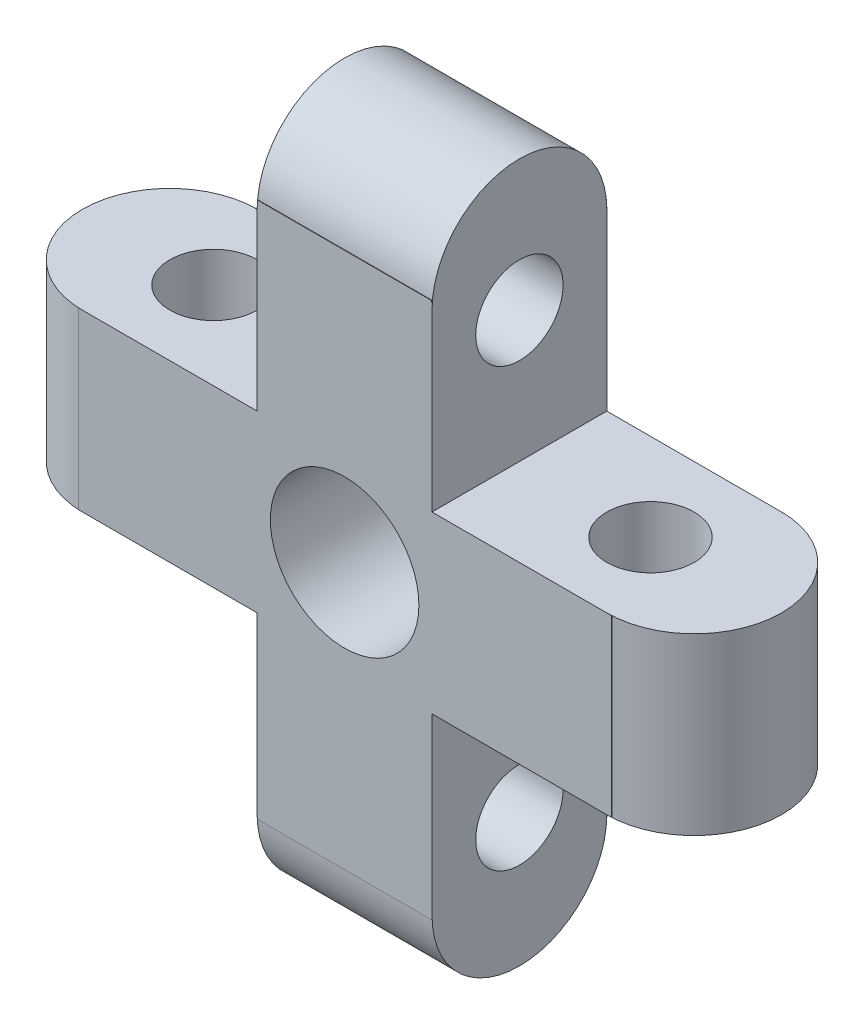
SolidWorks part; units mm, degrees
ref_plane "前视基准面" through (0, 0, 0) normal (0, 0, 1) x (1, 0, 0)
ref_plane "上视基准面" through (0, 0, 0) normal (0, 1, 0) x (1, 0, 0)
ref_plane "右视基准面" through (0, 0, 0) normal (1, 0, 0) x (0, 0, -1)
sketch "草图2" plane through (0, 0, 0) normal (0, 0, 1) x (1, 0, 0)
  line L0 (1.2374, 9.4816) -> (1.2374, 19.4816)
  line L1 (-8.7626, 9.4816) -> (1.2374, 9.4816)
  line L3 (-8.7626, -0.5184) -> (1.2374, -0.5184)
  line L5 (11.2374, 9.4816) -> (21.2374, 9.4816)
  line L8 (1.2374, -10.5184) -> (1.2374, -0.5184)
  line L10 (11.2374, -10.5184) -> (11.2374, -0.5184)
  line L14 (11.2374, -0.5184) -> (21.2374, -0.5184)
  line L18 (0, 0) -> (2.3667, -9.4816) construction
  line L19 (11.2374, 9.4816) -> (11.2374, 19.4816)
  line L20 (-8.7626, 9.4816) -> (1.2374, 9.4816)
  arc A0 (-8.7626, 9.4816) -> (-8.7626, -0.5184) centre (-8.7626, 4.4816) ccw
  arc A1 (21.2374, 9.4816) -> (21.2374, -0.5184) centre (21.2374, 4.4816) cw
  arc A2 (1.2374, -10.5184) -> (11.2374, -10.5184) centre (6.2374, -10.5184) ccw
  arc A3 (1.2374, 19.4816) -> (11.2374, 19.4816) centre (6.2374, 19.4816) cw
  point P0 (0, 0)
  point P5 (0, 0)
  dimension "D1" = 10
  dimension "D2" = 10
  dimension "D3" = 10
extrude "凸台-拉伸1" add sketch "草图2" along normal blind 10
sketch "草图3" plane through (0, -0.5184, 0) normal (0, -1, 0) x (1, 0, 0)
  line L0 (-8.7626, 0) -> (1.2374, 0) construction
  line L1 (1.2374, 0) -> (1.2374, 10) construction
  line L2 (1.2374, 10) -> (-8.7626, 10) construction
  line L3 (-13.7626, 0) -> (-8.7626, 0) construction
  line L4 (-8.7626, 10) -> (-13.7626, 10) construction
  line L5 (-8.7626, 10) -> (-8.7626, 0) construction
  line L6 (-8.7626, 0) -> (1.2374, 0)
  line L7 (1.2374, 0) -> (1.2374, 10)
  line L8 (1.2374, 10) -> (-8.7626, 10)
  line L9 (-13.7626, 0) -> (-8.7626, 0)
  line L10 (-8.7626, 10) -> (-13.7626, 10)
  line L11 (-8.7626, 10) -> (-8.7626, 0)
  line L12 (-13.7626, 10) -> (1.2374, 0)
  line L13 (-13.7626, 0) -> (1.2374, 10)
  circle A0 centre (-6.2626, 5) radius 2.5
  dimension "D1" = 5
extrude "切除-拉伸1" cut sketch "草图3" against normal blind 10 contours L12 A0 L13 | L12 A0 L13 | L13 A0 L12 | L13 A0 L12
sketch "草图4" plane through (11.2374, 0, 0) normal (1, 0, 0) x (0, 0, -1)
  line L0 (0, -15.5184) -> (0, -10.5184) construction
  line L1 (-10, -10.5184) -> (-10, -15.5184) construction
  line L2 (-10, -10.5184) -> (0, -10.5184) construction
  line L3 (0, -10.5184) -> (0, -0.5184) construction
  line L4 (0, -0.5184) -> (-10, -0.5184) construction
  line L5 (-10, -0.5184) -> (-10, -10.5184) construction
  line L6 (0, -15.5184) -> (0, -10.5184)
  line L7 (-10, -10.5184) -> (-10, -15.5184)
  line L8 (-10, -10.5184) -> (0, -10.5184)
  line L9 (0, -10.5184) -> (0, -0.5184)
  line L10 (0, -0.5184) -> (-10, -0.5184)
  line L11 (-10, -0.5184) -> (-10, -10.5184)
  line L12 (-10, -15.5184) -> (0, -0.5184)
  line L13 (0, -15.5184) -> (-10, -0.5184)
  circle A0 centre (-5, -8.0184) radius 2.5
  dimension "D1" = 5
extrude "切除-拉伸2" cut sketch "草图4" against normal blind 10 contours L13 A0 L12 | L12 A0 L13 | L13 A0 L12 | L12 A0 L13
sketch "草图5" plane through (0, 9.4816, 0) normal (0, 1, 0) x (1, 0, 0)
  line L0 (26.2374, 0) -> (21.2374, 0) construction
  line L1 (21.2374, -10) -> (26.2374, -10) construction
  line L2 (21.2374, -10) -> (21.2374, 0) construction
  line L3 (21.2374, 0) -> (11.2374, 0) construction
  line L4 (11.2374, 0) -> (11.2374, -10) construction
  line L5 (11.2374, -10) -> (21.2374, -10) construction
  line L6 (26.2374, 0) -> (21.2374, 0)
  line L7 (21.2374, -10) -> (26.2374, -10)
  line L8 (21.2374, -10) -> (21.2374, 0)
  line L9 (21.2374, 0) -> (11.2374, 0)
  line L10 (11.2374, 0) -> (11.2374, -10)
  line L11 (11.2374, -10) -> (21.2374, -10)
  line L12 (11.2374, 0) -> (26.2374, -10)
  line L13 (26.2374, 0) -> (11.2374, -10)
  circle A0 centre (18.7374, -5) radius 2.5
  dimension "D1" = 5
extrude "切除-拉伸3" cut sketch "草图5" against normal blind 10 contours L12 A0 L13 | L13 A0 L12 | L13 A0 L12 | L12 A0 L13
sketch "草图6" plane through (1.2374, 0, 0) normal (-1, 0, 0) x (0, 0, 1)
  line L0 (0, 24.4816) -> (0, 19.4816) construction
  line L1 (10, 19.4816) -> (10, 24.4816) construction
  line L3 (0, 19.4816) -> (0, 9.4816) construction
  line L4 (0, 9.4816) -> (10, 9.4816) construction
  line L5 (10, 9.4816) -> (10, 19.4816) construction
  line L6 (0, 24.4816) -> (0, 19.4816)
  line L7 (10, 19.4816) -> (10, 24.4816)
  line L9 (0, 19.4816) -> (0, 9.4816)
  line L10 (0, 9.4816) -> (10, 9.4816)
  line L11 (10, 9.4816) -> (10, 19.4816)
  line L12 (0, 9.4816) -> (10, 24.4816)
  line L13 (10, 9.4816) -> (0, 24.4816)
  circle A0 centre (5, 16.9816) radius 2.5
  dimension "D1" = 5
extrude "切除-拉伸4" cut sketch "草图6" against normal blind 10 contours L13 A0 L12 | L12 A0 L13 | L13 A0 L12 | L12 A0 L13
sketch "草图7" plane through (0, 0, 10) normal (0, 0, 1) x (1, 0, 0)
  line L0 (11.2374, 9.4816) -> (1.2374, -0.5184)
  line L1 (1.2374, 9.4816) -> (11.2374, -0.5184)
  line L8 (-8.7626, -0.5184) -> (1.2374, -0.5184)
  line L9 (1.2374, -0.5184) -> (1.2374, -10.5184)
  line L10 (11.2374, -10.5184) -> (11.2374, -0.5184)
  line L11 (11.2374, -0.5184) -> (21.2374, -0.5184)
  line L12 (21.2374, 9.4816) -> (11.2374, 9.4816)
  line L13 (11.2374, 9.4816) -> (11.2374, 19.4816)
  line L14 (1.2374, 19.4816) -> (1.2374, 9.4816)
  line L15 (1.2374, 9.4816) -> (-8.7626, 9.4816)
  line L16 (-8.7626, -0.5184) -> (1.2374, -0.5184)
  line L17 (1.2374, -0.5184) -> (1.2374, -10.5184)
  line L18 (11.2374, -10.5184) -> (11.2374, -0.5184)
  line L19 (11.2374, -0.5184) -> (21.2374, -0.5184)
  line L20 (21.2374, 9.4816) -> (11.2374, 9.4816)
  line L21 (11.2374, 9.4816) -> (11.2374, 19.4816)
  line L22 (1.2374, 19.4816) -> (1.2374, 9.4816)
  line L23 (1.2374, 9.4816) -> (-8.7626, 9.4816)
  circle A0 centre (6.2374, 4.4816) radius 3
  arc A4 (1.2374, -10.5184) -> (11.2374, -10.5184) centre (6.2374, -10.5184) ccw
  arc A5 (21.2374, -0.5184) -> (21.2374, 9.4816) centre (21.2374, 4.4816) ccw
  arc A6 (11.2374, 19.4816) -> (1.2374, 19.4816) centre (6.2374, 19.4816) ccw
  arc A7 (-8.7626, 9.4816) -> (-8.7626, -0.5184) centre (-8.7626, 4.4816) ccw
  arc A8 (1.2374, -10.5184) -> (11.2374, -10.5184) centre (6.2374, -10.5184) ccw
  arc A9 (21.2374, -0.5184) -> (21.2374, 9.4816) centre (21.2374, 4.4816) ccw
  arc A10 (11.2374, 19.4816) -> (1.2374, 19.4816) centre (6.2374, 19.4816) ccw
  arc A11 (-8.7626, 9.4816) -> (-8.7626, -0.5184) centre (-8.7626, 4.4816) ccw
  dimension "D2" = 6
  dimension "D1" = 0
extrude "切除-拉伸5" cut sketch "草图7" against normal blind 10 contours L0 A0 L1 | L1 A0 L0 | L0 A0 L1 | L1 A0 L0
sketch "草图8" plane through (0, 0, 10) normal (0, 0, 1) x (1, 0, 0)
  circle A0 centre (6.2374, 4.4816) radius 3 construction
  circle A1 centre (6.2374, 4.4816) radius 3
  circle A2 centre (6.2374, 4.4816) radius 4.25
  dimension "D1" = 8.5
extrude "切除-拉伸6" cut sketch "草图8" against normal through all
sketch "草图9" plane through (1.2374, 0, 0) normal (-1, 0, 0) x (0, 0, 1)
  line L0 (10, 19.9472) -> (0, 19.9472)
  line L4 (10, 19.4816) -> (10, 24.4816) construction
  line L5 (10, 19.9472) -> (10, 24.4816)
  line L6 (0, 24.4816) -> (0, 19.4816) construction
  line L7 (0, 24.4816) -> (0, 19.9472)
  line L8 (10, 24.4816) -> (0, 24.4816)
extrude "切除-拉伸7" cut sketch "草图9" against normal through all
sketch "草图10" plane through (1.2374, 0, 0) normal (-1, 0, 0) x (0, 0, 1)
  line L0 (10, 19.4816) -> (5, 19.4816) construction
  line L1 (5, 19.4816) -> (0, 19.4816) construction
  line L2 (10, 19.4816) -> (5, 19.4816)
  line L3 (5, 19.4816) -> (0, 19.4816)
  arc A0 (0, 19.4816) -> (10, 19.4816) centre (5, 19.4816) cw
extrude "凸台-拉伸2" add sketch "草图10" against normal blind 10
sketch "草图12" plane through (1.2374, 0, 0) normal (-1, 0, 0) x (0, 0, 1)
  line L5 (10, -15.5184) -> (10, -10.5184) construction
  line L6 (0, -10.5184) -> (0, -15.5184) construction
  line L7 (10, -15.5184) -> (10, -10.7367)
  line L8 (0, -10.7367) -> (0, -15.5184)
  line L9 (0, -15.5184) -> (10, -15.5184)
  line L10 (0, -10.7367) -> (10, -10.7367)
extrude "切除-拉伸8" cut sketch "草图12" against normal through all
sketch "草图13" plane through (1.2374, 0, 0) normal (-1, 0, 0) x (0, 0, 1)
  line L0 (10, -10.5184) -> (5, -10.5184) construction
  line L1 (5, -10.5184) -> (0, -10.5184) construction
  line L2 (10, -10.5184) -> (5, -10.5184)
  line L3 (5, -10.5184) -> (0, -10.5184)
  arc A0 (0, -10.5184) -> (10, -10.5184) centre (5, -10.5184) ccw
extrude "凸台-拉伸3" add sketch "草图13" against normal blind 10
sketch "草图15" plane through (0, 9.4816, 0) normal (0, 1, 0) x (1, 0, 0)
  line L0 (21.2374, -10) -> (26.2374, -10) construction
  line L1 (26.2374, 0) -> (21.2374, 0) construction
  line L2 (21.5181, -10) -> (26.2374, -10)
  line L3 (26.2374, 0) -> (21.5181, 0)
  line L4 (-8.7626, 0) -> (-13.7626, 0) construction
  line L5 (-13.7626, -10) -> (-8.7626, -10) construction
  line L6 (-8.9963, 0) -> (-13.7626, 0)
  line L7 (-13.7626, -10) -> (-8.9963, -10)
  line L8 (-13.7626, 0) -> (-13.7626, -10)
  line L9 (26.2374, 0) -> (26.2374, -10)
  line L10 (21.5181, -10) -> (21.5181, 0)
  line L11 (-8.9963, -10) -> (-8.9963, 0)
extrude "切除-拉伸9" cut sketch "草图15" against normal through all
sketch "草图16" plane through (0, 9.4816, 0) normal (0, 1, 0) x (1, 0, 0)
  line L0 (21.2374, -5) -> (21.2374, 0) construction
  line L1 (21.2374, -10) -> (21.2374, -5) construction
  line L2 (21.2374, -5) -> (21.2374, 0)
  line L3 (21.2374, -10) -> (21.2374, -5)
  line L4 (-8.7626, -5) -> (-8.7626, 0) construction
  line L5 (-8.7626, -10) -> (-8.7626, -5) construction
  line L6 (-8.7626, -5) -> (-8.7626, 0)
  line L7 (-8.7626, -10) -> (-8.7626, -5)
  arc A0 (21.2374, -10) -> (21.2374, 0) centre (21.2374, -5) ccw
  arc A1 (-8.7626, -10) -> (-8.7626, 0) centre (-8.7626, -5) cw
extrude "凸台-拉伸4" add sketch "草图16" against normal blind 10
